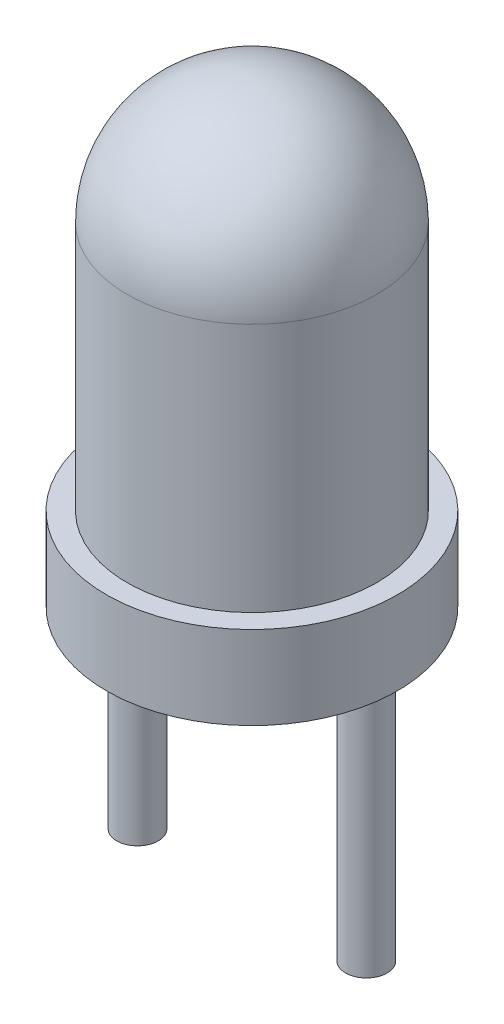
SolidWorks part; units mm, degrees
ref_plane "Front" through (0, 0, 0) normal (0, 0, 1) x (1, 0, 0)
ref_plane "Top" through (0, 0, 0) normal (0, 1, 0) x (1, 0, 0)
ref_plane "Right" through (0, 0, 0) normal (1, 0, 0) x (0, 0, -1)
sketch "Sketch1" plane through (0, 0, 0) normal (0, 0, 1) x (1, 0, 0)
  line L0 (0, 0) -> (-1.75, 0)
  line L1 (-1.75, 0) -> (-1.75, 1)
  line L2 (-1.75, 1) -> (-1.5, 1)
  line L3 (-1.5, 1) -> (-1.5, 4)
  line L4 (0, 5.5) -> (0, 0) construction
  line L5 (0, 0) -> (0, 5.5)
  arc A0 (-1.5, 4) -> (0, 5.5) centre (0, 4) cw
  dimension "D1" = 3.5
  dimension "D2" = 3
  dimension "D3" = 1
  dimension "D4" = 5.5
revolve "Revolve1" add sketch "Sketch1" angle 360 about L4
sketch "Sketch2" plane through (0, 0, 0) normal (0, -1, 0) x (1, 0, 0)
  line L0 (-1.375, 0) -> (1.375, 0) construction
  circle A0 centre (-1.375, 0) radius 0.25
  circle A1 centre (1.375, 0) radius 0.25
  dimension "D1" = 0.5
  dimension "D2" = 3
extrude "Boss-Extrude1" add sketch "Sketch2" along normal blind 3
